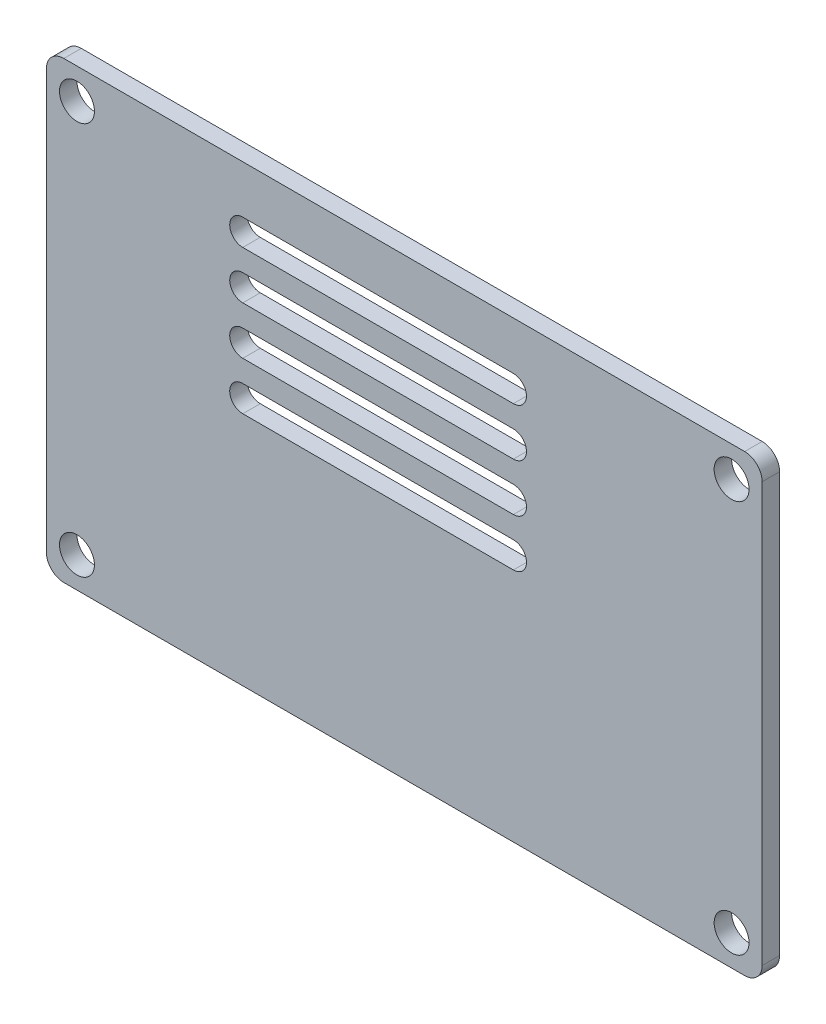
SolidWorks part; units mm, degrees
ref_plane "Front" through (0, 0, 0) normal (0, 0, 1) x (1, 0, 0)
ref_plane "Top" through (0, 0, 0) normal (0, 1, 0) x (1, 0, 0)
ref_plane "Right" through (0, 0, 0) normal (1, 0, 0) x (0, 0, -1)
sketch "Sketch1" plane through (0, 0, 0) normal (0, 0, 1) x (1, 0, 0)
  line L1 (41, -26) -> (-41, -26)
  line L2 (41, -26) -> (41, 26)
  line L3 (41, 26) -> (-41, 26)
  line L4 (-41, -26) -> (-41, 26)
  line L5 (41, -26) -> (-41, 26) construction
  line L6 (41, 26) -> (-41, -26) construction
  point P0 (0, 0)
  dimension "D1" = 82
  dimension "D2" = 52
extrude "Boss-Extrude1" add sketch "Sketch1" along normal blind 2
fillet "Fillet1" radius 2 4 edges at (41, -26, 1) (-41, -26, 1) (-41, 26, 1) (41, 26, 1)
sketch "Sketch2" plane through (0, 0, 2) normal (0, 0, 1) x (1, 0, 0)
  line L0 (-18.5, 19) -> (12.5, 19) construction
  line L1 (-18.5, 20.5) -> (12.5, 20.5)
  line L2 (-18.5, 17.5) -> (12.5, 17.5)
  line L3 (39, 26) -> (-39, 26) construction
  line L4 (-41, 24) -> (-41, -24) construction
  line L5 (-18.5, 13.5) -> (12.5, 13.5) construction
  line L6 (-18.5, 15) -> (12.5, 15)
  line L7 (-18.5, 12) -> (12.5, 12)
  line L8 (-18.5, 8) -> (12.5, 8) construction
  line L9 (-18.5, 9.5) -> (12.5, 9.5)
  line L10 (-18.5, 6.5) -> (12.5, 6.5)
  line L11 (-18.5, 2.5) -> (12.5, 2.5) construction
  line L12 (-18.5, 4) -> (12.5, 4)
  line L13 (-18.5, 1) -> (12.5, 1)
  arc A0 (-18.5, 20.5) -> (-18.5, 17.5) centre (-18.5, 19) ccw
  arc A1 (12.5, 17.5) -> (12.5, 20.5) centre (12.5, 19) ccw
  arc A2 (-18.5, 15) -> (-18.5, 12) centre (-18.5, 13.5) ccw
  arc A3 (12.5, 12) -> (12.5, 15) centre (12.5, 13.5) ccw
  arc A4 (-18.5, 9.5) -> (-18.5, 6.5) centre (-18.5, 8) ccw
  arc A5 (12.5, 6.5) -> (12.5, 9.5) centre (12.5, 8) ccw
  arc A6 (-18.5, 4) -> (-18.5, 1) centre (-18.5, 2.5) ccw
  arc A7 (12.5, 1) -> (12.5, 4) centre (12.5, 2.5) ccw
  point P2 (-3, 19)
  point P14 (-3, 13.5)
  point P20 (-3, 8)
  point P27 (-3, 2.5)
  dimension "D1" = 34
  dimension "D2" = 3
  dimension "D3" = 5.5
  dimension "D4" = 21
  dimension "D5" = 4
extrude "Cut-Extrude1" cut sketch "Sketch2" against normal through all
sketch "Sketch3" plane through (0, 0, 2) normal (0, 0, 1) x (1, 0, 0)
  line L0 (37.5, 22.5) -> (37.5, -22.5) construction
  line L1 (37.5, -22.5) -> (-37.5, -22.5) construction
  line L2 (-37.5, -22.5) -> (-37.5, 22.5) construction
  line L3 (-37.5, 22.5) -> (37.5, 22.5) construction
  circle A0 centre (37.5, 22.5) radius 2
  circle A1 centre (-37.5, 22.5) radius 2
  circle A2 centre (37.5, -22.5) radius 2
  circle A3 centre (-37.5, -22.5) radius 2
  point P8 (0, -22.5)
  point P9 (37.5, 0)
  dimension "D3" = 4
  dimension "D1" = 75
  dimension "D2" = 45
extrude "Cut-Extrude2" cut sketch "Sketch3" against normal through all
